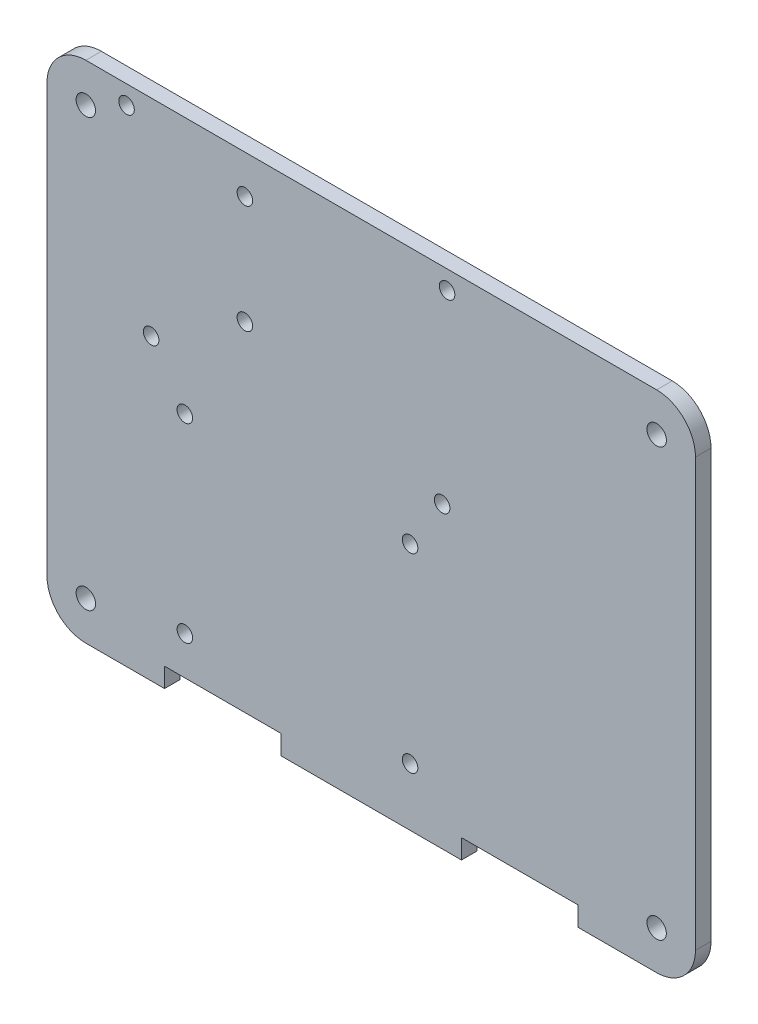
SolidWorks part; units mm, degrees
ref_plane "Front Plane" through (0, 0, 0) normal (0, 0, 1) x (1, 0, 0)
ref_plane "Top Plane" through (0, 0, 0) normal (0, 1, 0) x (1, 0, 0)
ref_plane "Right Plane" through (0, 0, 0) normal (1, 0, 0) x (0, 0, -1)
sketch "Sketch1" plane through (0, 0, 0) normal (0, 0, 1) x (1, 0, 0)
  line L1 (-83.5, 65) -> (83.5, 65)
  line L2 (-83.5, 65) -> (-83.5, -65)
  line L3 (-83.5, -65) -> (83.5, -65)
  line L4 (83.5, 65) -> (83.5, -65)
  line L5 (-83.5, 65) -> (83.5, -65) construction
  line L6 (-83.5, -65) -> (83.5, 65) construction
  point P0 (0, 0)
  dimension "D1" = 130
  dimension "D2" = 167
extrude "Boss-Extrude1" add sketch "Sketch1" along normal blind 4
fillet "Fillet1" radius 10 2 edges at (-83.5, -65, 2) (-83.5, 65, 2)
fillet "Fillet2" radius 10 2 edges at (83.5, -65, 2) (83.5, 65, 2)
sketch "Sketch4" plane through (0, 0, 4) normal (0, 0, 1) x (1, 0, 0)
  line L0 (73.5, 65) -> (-73.5, 65) construction
  line L1 (8.5, 35) -> (23.5, 35)
  line L2 (8.5, 35) -> (8.5, -15)
  line L3 (8.5, -15) -> (23.5, -15)
  line L4 (23.5, 35) -> (23.5, -15)
  line L5 (8.5, 35) -> (23.5, -15) construction
  line L6 (8.5, -15) -> (23.5, 35) construction
  line L7 (83.5, -55) -> (83.5, 55) construction
  point P0 (16, 10)
  dimension "D1" = 50
  dimension "D2" = 30
  dimension "D3" = 60
  dimension "D4" = 15
extrude "Cut-Extrude3" [suppressed] cut sketch "Sketch4" against normal blind 70
sketch "Sketch5" plane through (0, 0, 4) normal (0, 0, 1) x (1, 0, 0)
  circle A0 centre (-73.5, 55) radius 2.5
  circle A1 centre (73.5, 55) radius 2.5
  circle A2 centre (-73.5, -55) radius 2.5
  circle A3 centre (73.5, -55) radius 2.5
  dimension "D1" = 5
extrude "Cut-Extrude4" cut sketch "Sketch5" against normal blind 70
sketch "Sketch6" plane through (0, 0, 4) normal (0, 0, 1) x (1, 0, 0)
  line L0 (-73.5, -65) -> (73.5, -65) construction
  line L1 (-53.2338, -65) -> (-23.2338, -65)
  line L2 (-53.2338, -65) -> (-53.2338, -60)
  line L3 (-53.2338, -60) -> (-23.2338, -60)
  line L4 (-23.2338, -65) -> (-23.2338, -60)
  line L5 (-23.2338, -65) -> (-23.2338, -60) construction
  line L6 (-23.2338, -60) -> (-53.2338, -60) construction
  line L7 (0, 74.2879) -> (0, -19.3747) construction
  line L8 (53.2338, -60) -> (23.2338, -60)
  line L9 (53.2338, -65) -> (53.2338, -60)
  line L10 (53.2338, -65) -> (23.2338, -65)
  line L11 (23.2338, -65) -> (23.2338, -60)
  dimension "D1" = 5
extrude "Cut-Extrude5" cut sketch "Sketch6" against normal blind 10
sketch "Sketch7" plane through (0, 0, 4) normal (0, 0, 1) x (1, 0, 0)
  circle A0 centre (22.0068, -15.3143) radius 2
  circle A1 centre (59.3863, -15.3143) radius 2
  circle A2 centre (59.3863, -52.0561) radius 2
  circle A3 centre (22.0068, -52.0561) radius 2
  dimension "D1" = 4
extrude "Cut-Extrude6" [suppressed] cut sketch "Sketch7" against normal through all
sketch "Sketch8" plane through (0, 0, 4) normal (0, 0, 1) x (1, 0, 0)
  circle A0 centre (21.25, 56.5) radius 2
  circle A1 centre (60.25, 56.5) radius 2
  circle A2 centre (60.25, 3.5) radius 2
  circle A3 centre (21.25, 3.5) radius 2
  dimension "D1" = 4
extrude "Cut-Extrude7" [suppressed] cut sketch "Sketch8" against normal through all
sketch "Sketch9" plane through (0, 0, 4) normal (0, 0, 1) x (1, 0, 0)
  line L0 (83.5, -55) -> (83.5, 55) construction
  line L1 (-0.5, 35) -> (16.5, 35)
  line L2 (-0.5, 35) -> (-0.5, -35)
  line L3 (-0.5, -35) -> (16.5, -35)
  line L4 (16.5, 35) -> (16.5, -35)
  line L5 (-0.5, 35) -> (16.5, -35) construction
  line L6 (-0.5, -35) -> (16.5, 35) construction
  point P0 (8, 0)
  point P7 (83.5, 0)
  dimension "D1" = 17
  dimension "D2" = 70
  dimension "D3" = 67
extrude "Cut-Extrude8" [suppressed] cut sketch "Sketch9" against normal through all
sketch "Sketch10" plane through (0, 0, 4) normal (0, 0, 1) x (1, 0, 0)
  circle A0 centre (-48, -1.1062) radius 2
  circle A1 centre (10, -50.1062) radius 2
  circle A2 centre (-48, -50.1062) radius 2
  circle A3 centre (10, -1.1062) radius 2
  dimension "D1" = 4
extrude "Cut-Extrude9" cut sketch "Sketch10" against normal through all
sketch "Sketch11" plane through (0, 0, 4) normal (0, 0, 1) x (1, 0, 0)
  circle A0 centre (-63.02, 60.1902) radius 2
  circle A2 centre (-32.54, 55.1102) radius 2
  circle A4 centre (-32.54, 27.1702) radius 2
  circle A5 centre (19.53, 60.1902) radius 2
  circle A6 centre (18.26, 11.9302) radius 2
  circle A7 centre (-56.67, 11.9302) radius 2
  dimension "D1" = 4
extrude "Cut-Extrude10" cut sketch "Sketch11" against normal through all
